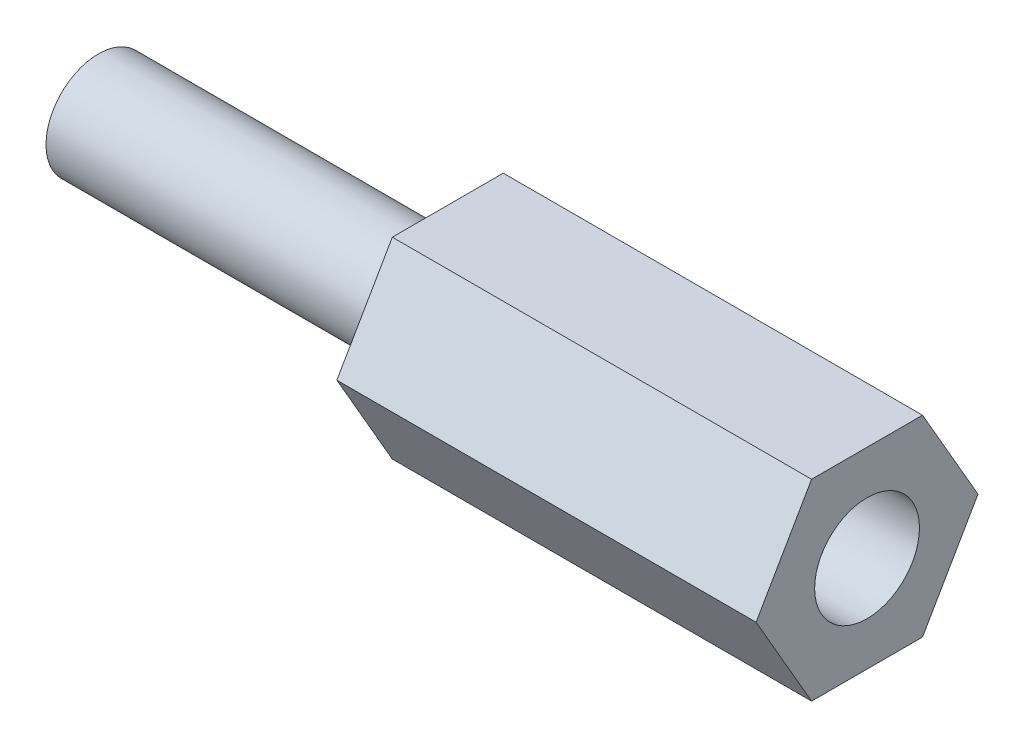
SolidWorks part; units mm, degrees
ref_plane "Front Plane" through (0, 0, 0) normal (0, 0, 1) x (1, 0, 0)
ref_plane "Top Plane" through (0, 0, 0) normal (0, 1, 0) x (1, 0, 0)
ref_plane "Right Plane" through (0, 0, 0) normal (1, 0, 0) x (0, 0, -1)
sketch "Sketch2" plane through (0, 0, 0) normal (1, 0, 0) x (0, 0, -1)
  line L1 (1.5877, 2.75) -> (-1.5877, 2.75)
  line L2 (-1.5877, 2.75) -> (-3.1754, 0)
  line L3 (-3.1754, 0) -> (-1.5877, -2.75)
  line L4 (-1.5877, -2.75) -> (1.5877, -2.75)
  line L5 (1.5877, -2.75) -> (3.1754, 0)
  line L6 (3.1754, 0) -> (1.5877, 2.75)
  circle A0 centre (0, 0) radius 2.75 construction
  circle A1 centre (0, 0) radius 1.5
  dimension "D2" = 3
  dimension "D1" = 5.5
extrude "Boss-Extrude1" add sketch "Sketch2" along normal blind 12
sketch "Sketch3" plane through (0, 0, 0) normal (-1, 0, 0) x (0, 0, 1)
  circle A0 centre (0, 0) radius 1.5
  circle A1 centre (0, 0) radius 1.5 construction
extrude "Boss-Extrude2" add sketch "Sketch3" along normal blind 10 and the other way blind 2
